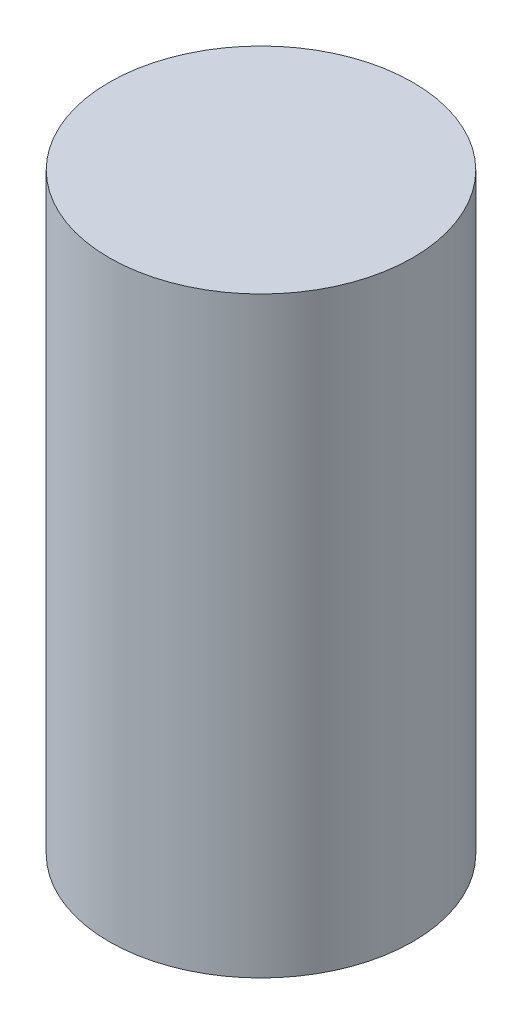
SolidWorks part; units mm, degrees
ref_plane "Front Plane" through (0, 0, 0) normal (0, 0, 1) x (1, 0, 0)
ref_plane "Top Plane" through (0, 0, 0) normal (0, 1, 0) x (1, 0, 0)
ref_plane "Right Plane" through (0, 0, 0) normal (1, 0, 0) x (0, 0, -1)
sketch "Sketch1" plane through (0, 0, 0) normal (0, 1, 0) x (1, 0, 0)
  circle A0 centre (0, 0) radius 2.54
  dimension "D1" = 5.08
extrude "Boss-Extrude1" add sketch "Sketch1" along normal blind 9.906
equation "\"pin diamiter\"= 5mm"
equation "\"pin length\"= 10mm"
equation "\"D1@Sketch1\"=\"pin diamiter\""
equation "\"D1@Boss-Extrude1\"=\"pin length\""
